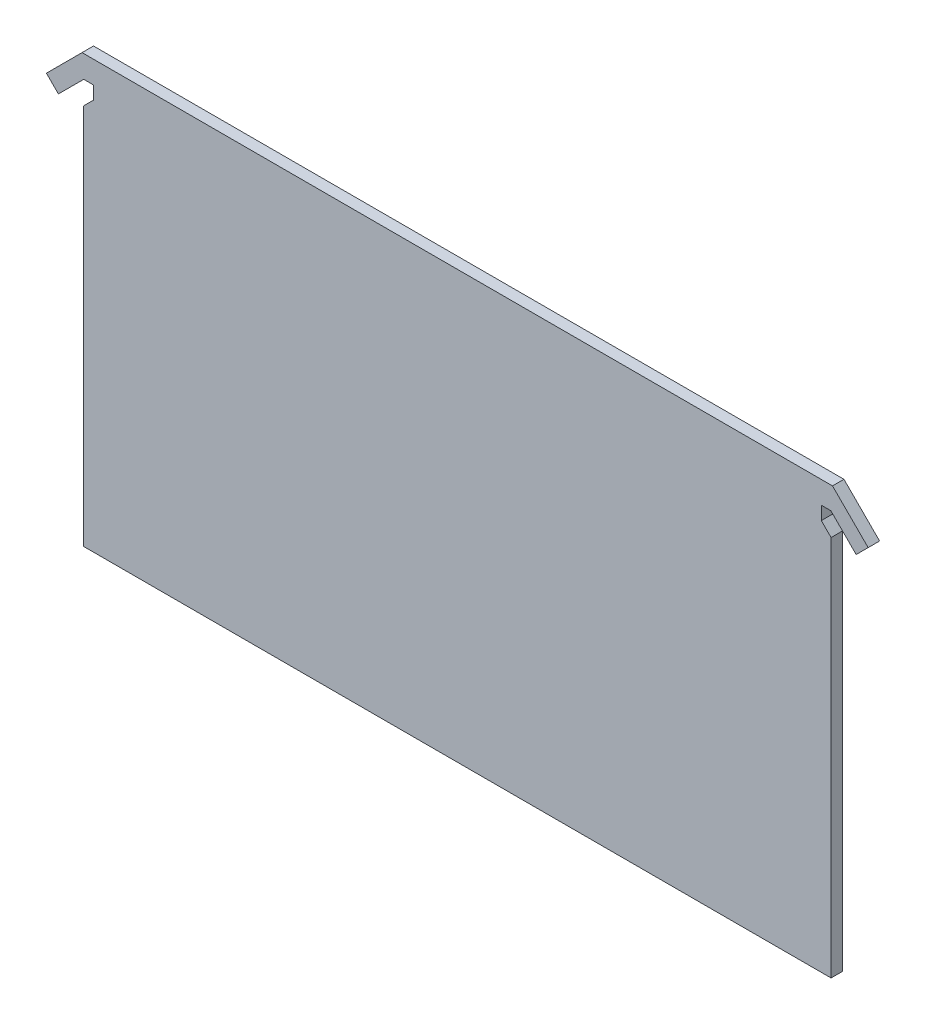
SolidWorks part; units mm, degrees
material "Acrylic (Medium-high impact)"
ref_plane "Front Plane" through (0, 0, 0) normal (0, 0, 1) x (1, 0, 0)
ref_plane "Top Plane" through (0, 0, 0) normal (0, 1, 0) x (1, 0, 0)
ref_plane "Right Plane" through (0, 0, 0) normal (1, 0, 0) x (0, 0, -1)
sketch "Sketch1" plane through (0, 0, 0) normal (0, 0, 1) x (1, 0, 0)
  line L0 (163.7412, 121.0167) -> (-153.7024, 121.0167)
  line L1 (-153.7024, 121.0167) -> (-191.7063, 121.0167)
  line L2 (-190.9553, 97.1919) -> (-190.9553, -102.7953)
  line L3 (-190.9553, -102.7953) -> (200.9942, -102.7953)
  line L4 (-190.8306, 109.3167) -> (-185.8306, 109.3167)
  line L5 (201.7451, 121.0167) -> (220.43, 102.3318)
  line L6 (5.0194, 116.0167) -> (5.0194, -97.3333) construction
  line L7 (-190.9553, 97.1919) -> (-185.8306, 102.3167)
  line L8 (-185.8306, 102.3167) -> (-185.8306, 109.3167)
  line L9 (200.8694, 109.3167) -> (214.1421, 96.044)
  line L10 (214.1421, 96.044) -> (220.43, 102.3318)
  line L11 (195.8694, 102.3167) -> (195.8694, 109.3167)
  line L12 (200.9942, 97.1919) -> (195.8694, 102.3167)
  line L13 (200.8694, 109.3167) -> (195.8694, 109.3167)
  line L14 (163.7412, 121.0167) -> (201.7451, 121.0167)
  line L17 (200.9942, 97.1919) -> (200.9942, -102.7953)
  line L22 (-204.1033, 96.044) -> (-210.3912, 102.3318)
  line L24 (-190.8306, 109.3167) -> (-204.1033, 96.044)
  line L29 (-191.7063, 121.0167) -> (-210.3912, 102.3318)
extrude "Boss-Extrude1" add sketch "Sketch1" along normal blind 6
